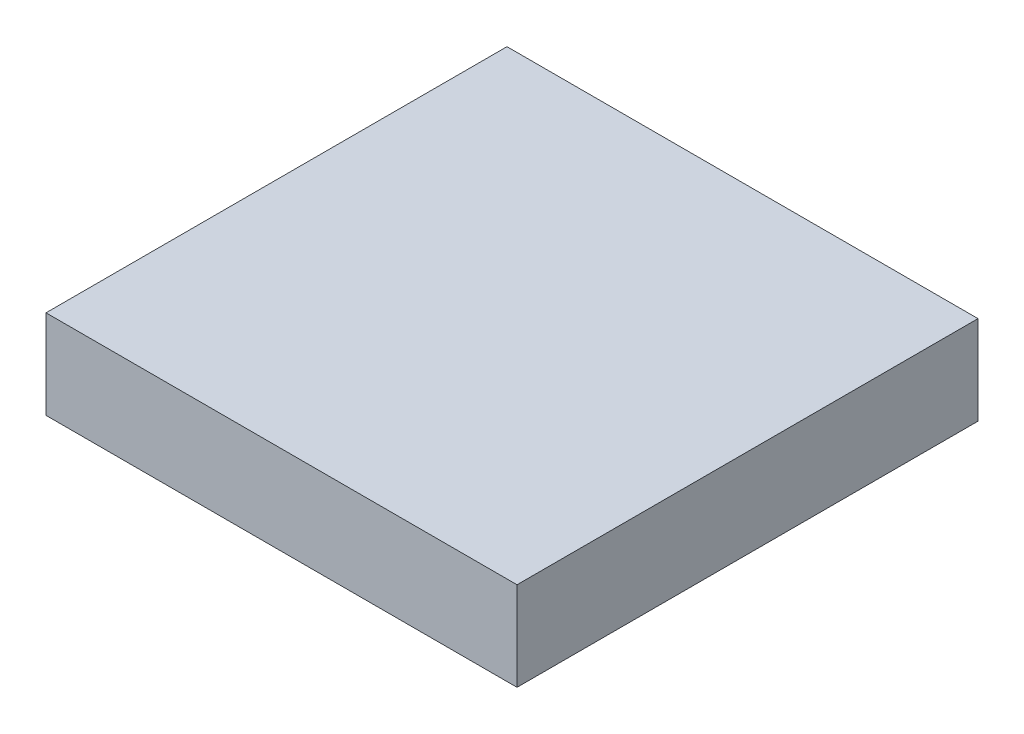
SolidWorks part; units mm, degrees
ref_plane "Front Plane" through (0, 0, 0) normal (0, 0, 1) x (1, 0, 0)
ref_plane "Top Plane" through (0, 0, 0) normal (0, 1, 0) x (1, 0, 0)
ref_plane "Right Plane" through (0, 0, 0) normal (1, 0, 0) x (0, 0, -1)
sketch "Sketch1" plane through (0, 0, 0) normal (0, 1, 0) x (1, 0, 0)
  line L1 (-91.45, 89.5) -> (91.45, 89.5)
  line L2 (-91.45, 89.5) -> (-91.45, -89.5)
  line L3 (-91.45, -89.5) -> (91.45, -89.5)
  line L4 (91.45, 89.5) -> (91.45, -89.5)
  line L5 (0, -89.5) -> (0, 89.5) construction
  line L6 (-91.45, 0) -> (91.45, 0) construction
  point P0 (0, 0)
  dimension "D1" = 179
  dimension "D2" = 182.9
extrude "Boss-Extrude1" add sketch "Sketch1" along normal blind 34.5
